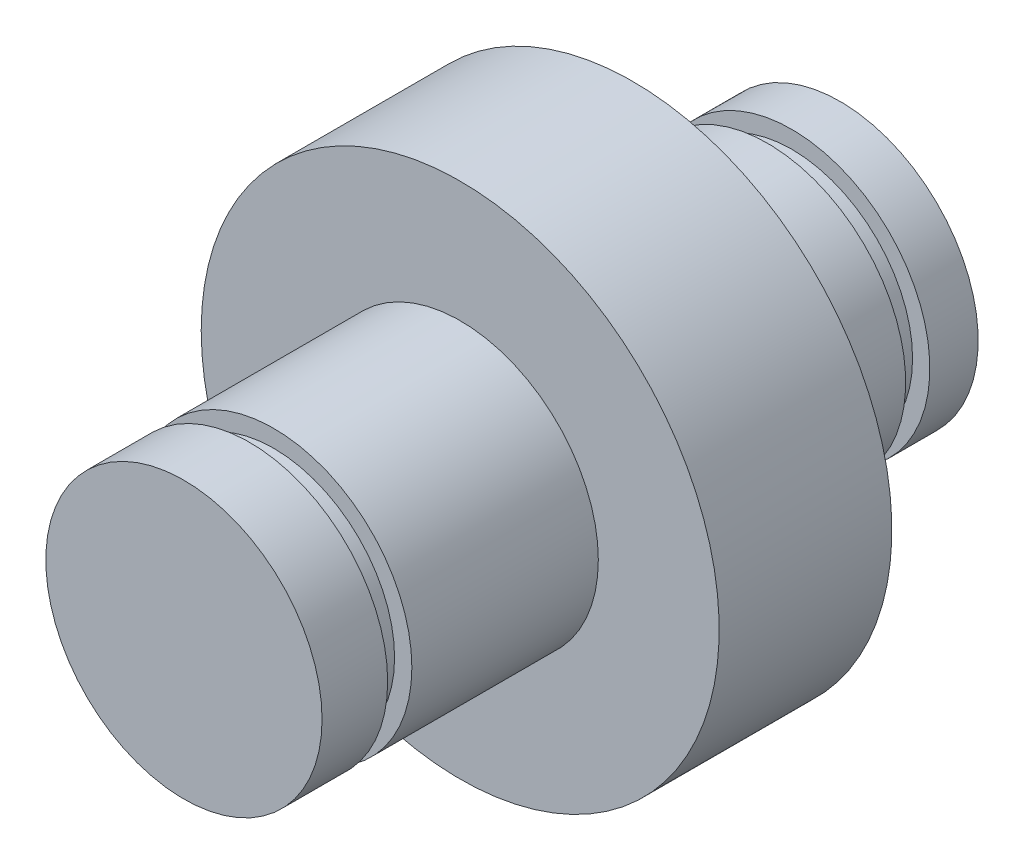
SolidWorks part; units mm, degrees
ref_plane "Front Plane" through (0, 0, 0) normal (0, 0, 1) x (1, 0, 0)
ref_plane "Top Plane" through (0, 0, 0) normal (0, 1, 0) x (1, 0, 0)
ref_plane "Right Plane" through (0, 0, 0) normal (1, 0, 0) x (0, 0, -1)
sketch "Sketch1" plane through (0, 0, 0) normal (0, 0, 1) x (1, 0, 0)
  circle A0 centre (0, 0) radius 4
  dimension "D1" = 8
extrude "Boss-Extrude1" add sketch "Sketch1" along normal blind 8
sketch "Sketch2" plane through (0, 0, 0) normal (0, 0, -1) x (-1, 0, 0)
  circle A0 centre (0, 0) radius 7.5
  dimension "D1" = 15
extrude "Boss-Extrude2" add sketch "Sketch2" along normal blind 5
sketch "Sketch4" plane through (0, 0, -5) normal (0, 0, -1) x (-1, 0, 0)
  circle A0 centre (0, 0) radius 4
  dimension "D1" = 8
extrude "Boss-Extrude4" add sketch "Sketch4" along normal blind 6
sketch "Sketch5" plane through (0, 0, 0) normal (0, 1, 0) x (1, 0, 0)
  line L0 (-4, 0) -> (-4, -8) construction
  line L1 (-4, 0) -> (-4, -8)
  line L2 (-7.5, 0) -> (7.5, 0) construction
  line L3 (-4, -6.1) -> (-3.5, -6.1)
  line L4 (-4, -6.1) -> (-4, -5.4)
  line L5 (-4, -5.4) -> (-3.5, -5.4)
  line L6 (-3.5, -6.1) -> (-3.5, -5.4)
  line L7 (-4, -8) -> (4, -8) construction
  line L8 (-4, -8) -> (4, -8)
  line L9 (0, -8) -> (0, -5.8632) construction
  dimension "D1" = 0.5
  dimension "D2" = 0.7
  dimension "D3" = 6.1
revolve "Cut-Revolve3" cut sketch "Sketch5" angle 360 about L9
sketch "Sketch6" plane through (0, 0, 0) normal (0, 1, 0) x (1, 0, 0)
  line L0 (-4, 11) -> (-4, 5) construction
  line L1 (-4, 11) -> (-4, 5)
  line L2 (4, 11) -> (-4, 11) construction
  line L3 (4, 11) -> (-4, 11)
  line L4 (0, 11) -> (0, 4.6684) construction
  line L5 (7.5, 5) -> (-7.5, 5) construction
  line L6 (-4, 8.9) -> (-3.5, 8.9)
  line L7 (-4, 8.9) -> (-4, 9.6)
  line L8 (-4, 9.6) -> (-3.5, 9.6)
  line L9 (-3.5, 8.9) -> (-3.5, 9.6)
  dimension "D1" = 0.7
  dimension "D2" = 0.5
  dimension "D3" = 4.6
revolve "Cut-Revolve4" cut sketch "Sketch6" angle 360 about L4
